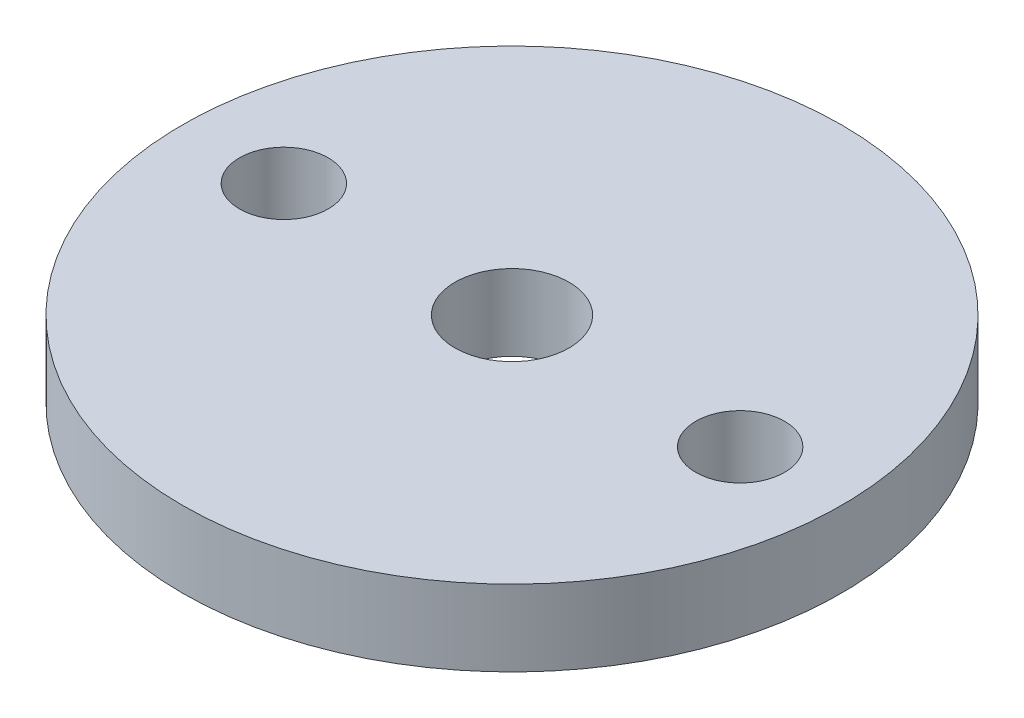
SolidWorks part; units mm, degrees
ref_plane "Front Plane" through (0, 0, 0) normal (0, 0, 1) x (1, 0, 0)
ref_plane "Top Plane" through (0, 0, 0) normal (0, 1, 0) x (1, 0, 0)
ref_plane "Right Plane" through (0, 0, 0) normal (1, 0, 0) x (0, 0, -1)
sketch "Sketch1" plane through (0, 0, 0) normal (0, 1, 0) x (1, 0, 0)
  circle A0 centre (0, 0) radius 13
  dimension "D1" = 26
extrude "Boss-Extrude1" add sketch "Sketch1" along normal blind 3
sketch "Sketch3" plane through (0, 3, 0) normal (0, 1, 0) x (1, 0, 0)
  circle A0 centre (0, 0) radius 2.25
  dimension "D1" = 4.5
extrude "Cut-Extrude1" cut sketch "Sketch3" against normal blind 3 contours A0
sketch "Sketch2" plane through (0, 3, 0) normal (0, 1, 0) x (1, 0, 0)
  circle A0 centre (9, 0) radius 1.75
  circle A1 centre (0, 0) radius 2.25 construction
  dimension "D1" = 3.5
  dimension "D2" = 9
extrude "Cut-Extrude2" cut sketch "Sketch2" against normal blind 3 contours A0
mirror "Mirror1" about plane through (0, 0, 0) normal (1, 0, 0) of "Cut-Extrude2"
